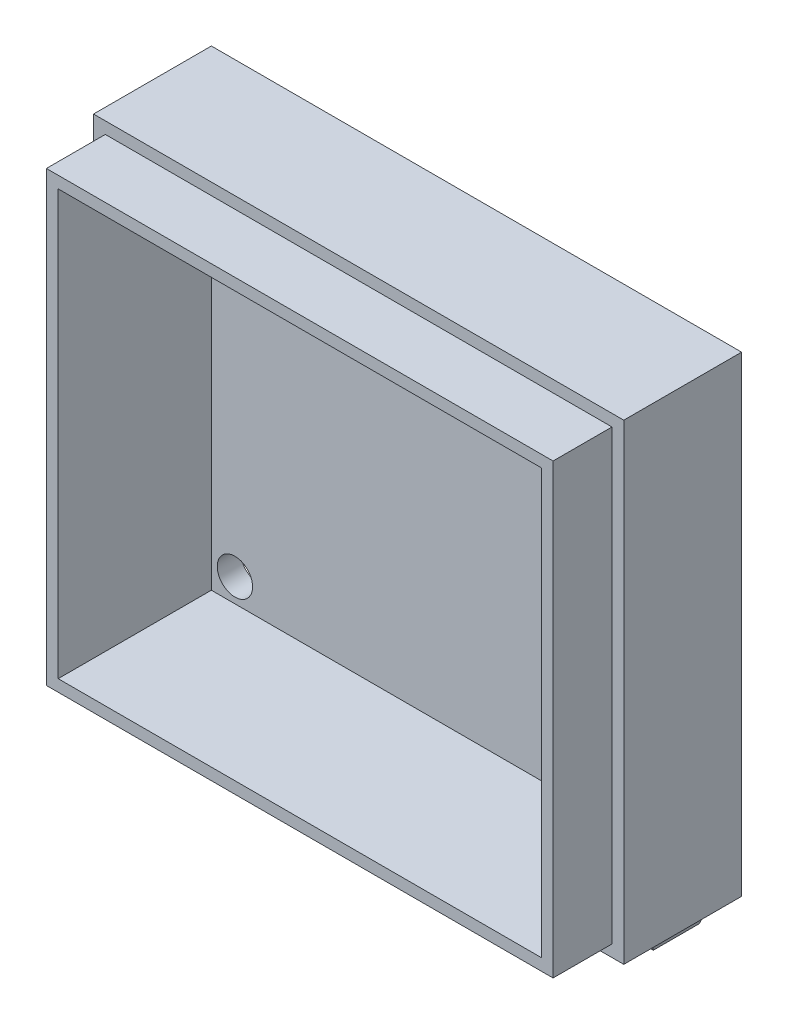
SolidWorks part; units mm, degrees
ref_plane "Front Plane" through (0, 0, 0) normal (0, 0, 1) x (1, 0, 0)
ref_plane "Top Plane" through (0, 0, 0) normal (0, 1, 0) x (1, 0, 0)
ref_plane "Right Plane" through (0, 0, 0) normal (1, 0, 0) x (0, 0, -1)
sketch "Sketch1" plane through (0, 0, 0) normal (0, 0, 1) x (1, 0, 0)
  line L1 (-45, -40) -> (45, -40)
  line L2 (-45, -40) -> (-45, 40)
  line L3 (-45, 40) -> (45, 40)
  line L4 (45, -40) -> (45, 40)
  line L5 (-45, -40) -> (45, 40) construction
  line L6 (-45, 40) -> (45, -40) construction
  point P0 (0, 0)
  dimension "D1" = 90
  dimension "D2" = 80
extrude "Boss-Extrude1" add sketch "Sketch1" along normal blind 30
shell "Shell1" thickness 4
sketch "Sketch4" plane through (0, -40, 0) normal (0, -1, 0) x (1, 0, 0)
  line L0 (-45, 0) -> (45, 0) construction
  line L1 (-42.5, 12.5) -> (-35.5, 12.5)
  line L2 (-42.5, 12.5) -> (-42.5, 2.5)
  line L3 (-42.5, 2.5) -> (-35.5, 2.5)
  line L4 (-35.5, 12.5) -> (-35.5, 2.5)
  line L5 (-45, 30) -> (-45, 0) construction
  line L6 (35.5, 12.5) -> (42.5, 12.5)
  line L7 (35.5, 12.5) -> (35.5, 2.5)
  line L8 (35.5, 2.5) -> (42.5, 2.5)
  line L9 (42.5, 12.5) -> (42.5, 2.5)
  line L10 (45, 30) -> (45, 0) construction
  dimension "D1" = 10
  dimension "D2" = 7
  dimension "D3" = 2.5
  dimension "D4" = 2.5
  dimension "D5" = 10
  dimension "D6" = 7
  dimension "D7" = 2.5
  dimension "D8" = 2.5
extrude "Boss-Extrude2" add sketch "Sketch4" along normal blind 4 draft 15
sketch "Sketch6" plane through (0, 0, 4) normal (0, 0, 1) x (1, 0, 0)
  line L0 (-41, -36) -> (41, -36) construction
  line L1 (-41, 36) -> (-41, -36) construction
  circle A0 centre (-37, -32) radius 3
  dimension "D1" = 4
  dimension "D2" = 4
extrude "Cut-Extrude3" cut sketch "Sketch6" against normal blind 10
sketch "Sketch8" plane through (0, 0, 30) normal (0, 0, 1) x (1, 0, 0)
  line L0 (43, -38) -> (43, 38)
  line L1 (43, 38) -> (-43, 38)
  line L2 (-43, 38) -> (-43, -38)
  line L3 (-43, -38) -> (43, -38)
  line L4 (45, -40) -> (45, 40)
  line L5 (45, 40) -> (-45, 40)
  line L6 (-45, 40) -> (-45, -40)
  line L7 (-45, -40) -> (45, -40)
  line L8 (45, -40) -> (45, 40)
  line L9 (45, 40) -> (-45, 40)
  line L10 (-45, 40) -> (-45, -40)
  line L11 (-45, -40) -> (45, -40)
  dimension "D1" = 0
  dimension "D2" = 2
extrude "Cut-Extrude4" cut sketch "Sketch8" against normal blind 10
